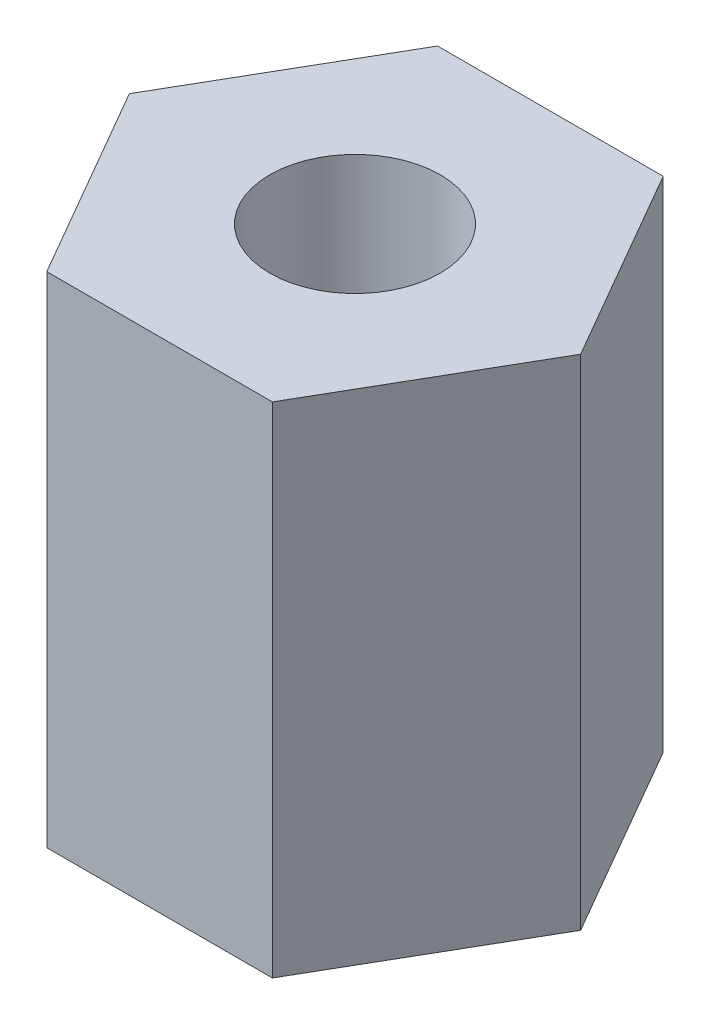
SolidWorks part; units mm, degrees
ref_plane "Front Plane" through (0, 0, 0) normal (0, 0, 1) x (1, 0, 0)
ref_plane "Top Plane" through (0, 0, 0) normal (0, 1, 0) x (1, 0, 0)
ref_plane "Right Plane" through (0, 0, 0) normal (1, 0, 0) x (0, 0, -1)
ref_plane "Plane1" through (0, 6, 0) normal (0, 1, 0) x (1, 0, 0)
sketch "Sketch1" plane through (0, 6, 0) normal (0, 1, 0) x (1, 0, 0)
  line L0 (1.3568, -2.35) -> (2.7135, 0)
  line L1 (2.7135, 0) -> (1.3568, 2.35)
  line L2 (1.3568, 2.35) -> (-1.3568, 2.35)
  line L3 (-1.3568, 2.35) -> (-2.7135, 0)
  line L4 (-2.7135, 0) -> (-1.3568, -2.35)
  line L5 (-1.3568, -2.35) -> (1.3568, -2.35)
  circle A0 centre (0, 0) radius 2.7135 construction
  dimension "D1" = 4.7
extrude "Boss-Extrude1" add sketch "Sketch1" against normal blind 6
ref_plane "Plane2" through (0, 0, 0) normal (0, 0, -1) x (-1, 0, 0)
hole_wizard "Tap Drill for M2.5x0.45 Tap1" positions "Sketch4" profile "Sketch3" hole size "M2.5x0.45" standard "ANSI Metric"
sketch "Sketch4" plane through (0, 6, 0) normal (0, 1, 0) x (1, 0, 0)
  point P0 (0, 0)
sketch "Sketch3" plane through (0, 6, 0) normal (1, 0, 0) x (0, 0, 1)
  line L0 (0, 0) -> (0, 19)
  line L1 (0, 19) -> (1.025, 19)
  line L2 (1.025, 19) -> (1.025, 0)
  line L5 (1.025, 0) -> (0, 0)
  line L10 (0, 19) -> (-1.025, 19) construction
  line L11 (0, -6.35) -> (0, 107.95) construction
  dimension "Hole Dia." = 2.05
  dimension "Hole Depth" = 19
  dimension "Drill Angle" = 180
